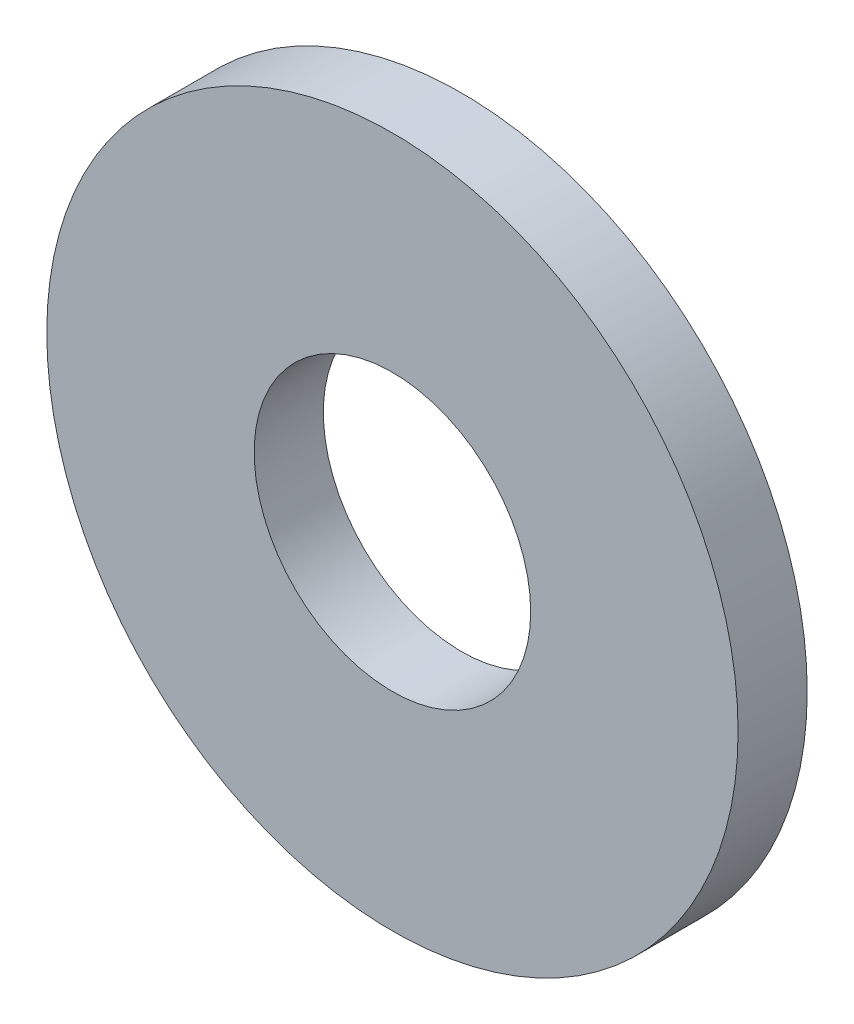
SolidWorks part; units mm, degrees
material "Delrin 2700 NC010, Low Viscosity Acetal Copolymer (SS)"
ref_plane "Front Plane" through (0, 0, 0) normal (0, 0, 1) x (1, 0, 0)
ref_plane "Top Plane" through (0, 0, 0) normal (0, 1, 0) x (1, 0, 0)
ref_plane "Right Plane" through (0, 0, 0) normal (1, 0, 0) x (0, 0, -1)
sketch "Sketch1" plane through (0, 0, 0) normal (0, 0, 1) x (1, 0, 0)
  circle A0 centre (0, 0) radius 7.9375
  circle A1 centre (0, 0) radius 3.175
  dimension "D1" = 15.875
  dimension "ID" = 6.35
extrude "Extrude1" add sketch "Sketch1" along normal mid plane 1.5875
sketch "Sketch2" plane through (0, 0, 0) normal (1, 0, 0) x (0, 0, -1)
  line L0 (-0.7937, -3.175) -> (0.7937, -3.175) construction
  line L3 (0.7937, 3.175) -> (-0.7937, 3.175) construction
  line L5 (-0.7937, -3.175) -> (0.7937, -3.175)
  line L6 (0.7937, 3.175) -> (-0.7937, 3.175)
sketch "Sketch4" plane through (0, 0, 0.7937) normal (0, 0, 1) x (1, 0, 0)
  line L0 (0, 0) -> (-2.2451, 2.2451)
  line L1 (0, -0.8731) -> (0, 0.8731) construction
  circle A0 centre (0, 0) radius 3.175 construction
  dimension "D1" = 45
